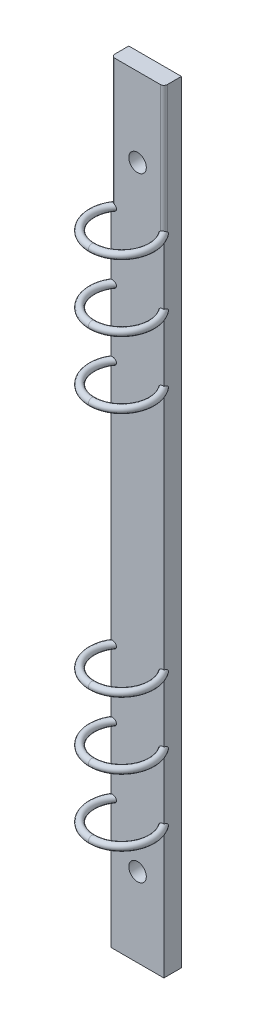
SolidWorks part; units mm, degrees
ref_plane "Front" through (0, 0, 0) normal (0, 0, 1) x (1, 0, 0)
ref_plane "Top" through (0, 0, 0) normal (0, 1, 0) x (1, 0, 0)
ref_plane "Right" through (0, 0, 0) normal (1, 0, 0) x (0, 0, -1)
sketch "Эскиз1" plane through (0, 0, 0) normal (0, 0, 1) x (1, 0, 0)
  line L0 (0, 0) -> (0, 87.5) construction
  line L5 (-7.5, -110) -> (7.5, -110)
  line L6 (-7.5, -110) -> (-7.5, 110)
  line L7 (-7.5, 110) -> (7.5, 110)
  line L8 (7.5, -110) -> (7.5, 110)
  line L9 (-7.5, -110) -> (7.5, 110) construction
  line L10 (-7.5, 110) -> (7.5, -110) construction
  line L11 (0, 0) -> (7.5, 0) construction
  circle A0 centre (0, 87.5) radius 2.5
  circle A1 centre (0, -87.5) radius 2.5
  point P0 (0, 0)
  dimension "D3" = 5
  dimension "D4" = 175
  dimension "D1" = 220
  dimension "D2" = 15
extrude "Бобышка-Вытянуть1" add sketch "Эскиз1" along normal blind 5
ref_plane "Плоскость1" through (0, 35, 0) normal (0, 1, 0) x (1, 0, 0)
sketch "Эскиз28" plane through (0, 35, 0) normal (0, 1, 0) x (1, 0, 0)
  line L0 (-7.5, 0) -> (7.5, 0) construction
  circle A0 centre (0, -9.5) radius 8.5
  dimension "D1" = 17
  dimension "D2" = 1
sweep "По траектории2" add path "Эскиз28" circular profile diameter 2 parameters "D3"=2
pattern_linear "Линейный массив4" count 3 spacing 19 along (0, 1, 0) of "По траектории2"
mirror "Зеркальное отражение1" about plane through (0, 0, 0) normal (0, 1, 0) of "Линейный массив4", "По траектории2"
fillet "Скругление1" radius 1 2 edges at (-7.5, 91.9846, 5) (7.5, 91.9846, 5)
sketch "Эскиз35" plane through (0, -110, 0) normal (0, -1, 0) x (1, 0, 0)
  line L0 (0, 0) -> (0, 19) construction
  dimension "D1" = 19
